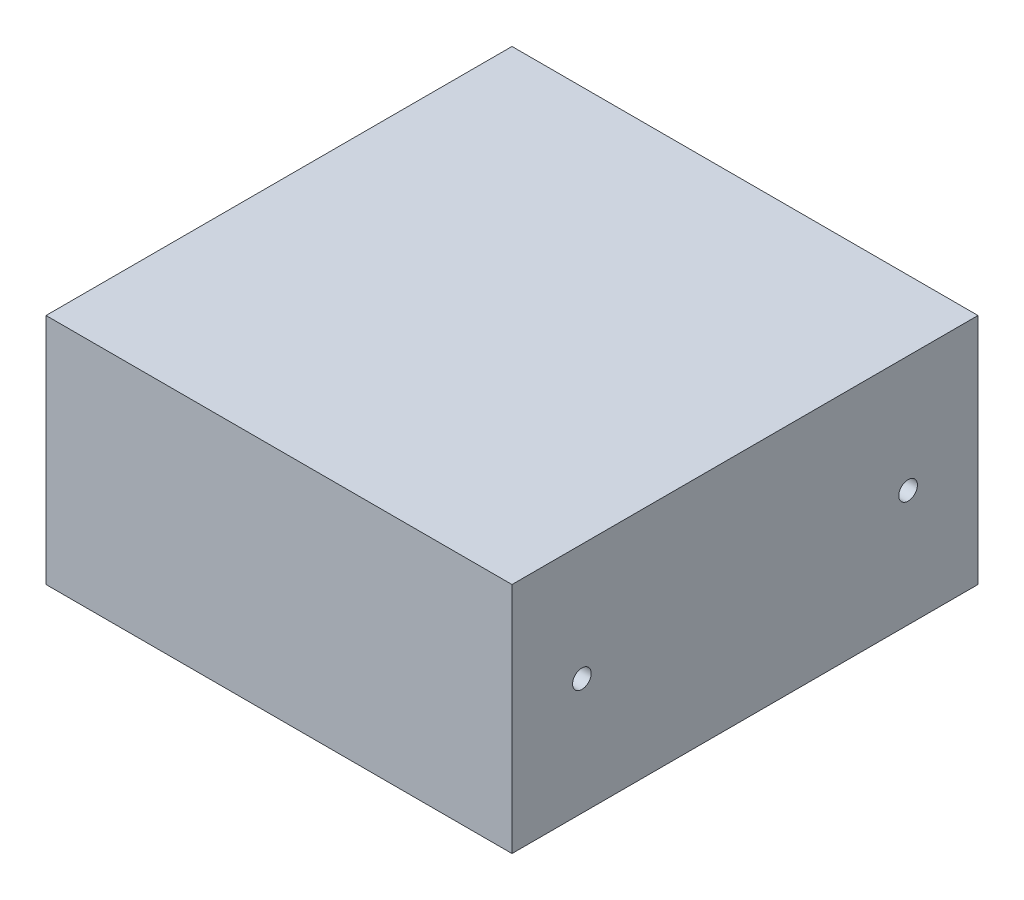
SolidWorks part; units mm, degrees
ref_plane "Front Plane" through (0, 0, 0) normal (0, 0, 1) x (1, 0, 0)
ref_plane "Top Plane" through (0, 0, 0) normal (0, 1, 0) x (1, 0, 0)
ref_plane "Right Plane" through (0, 0, 0) normal (1, 0, 0) x (0, 0, -1)
sketch "Sketch1" plane through (0, 0, 0) normal (0, 1, 0) x (1, 0, 0)
  line L1 (0, 0) -> (100, 0)
  line L2 (0, 0) -> (0, 100)
  line L3 (0, 100) -> (100, 100)
  line L4 (100, 0) -> (100, 100)
  dimension "D1" = 100
  dimension "D2" = 100
extrude "Boss-Extrude1" add sketch "Sketch1" along normal blind 50
sketch "Sketch2" plane through (100, 0, 0) normal (1, 0, 0) x (0, 0, -1)
  line L0 (100, 50) -> (100, 0) construction
  line L1 (0, 50) -> (0, 0) construction
  circle A0 centre (15, 25) radius 2
  circle A1 centre (85, 25) radius 2
  dimension "D1" = 4
  dimension "D2" = 4
  dimension "D3" = 15
  dimension "D4" = 15
extrude "Cut-Extrude1" cut sketch "Sketch2" against normal blind 10
